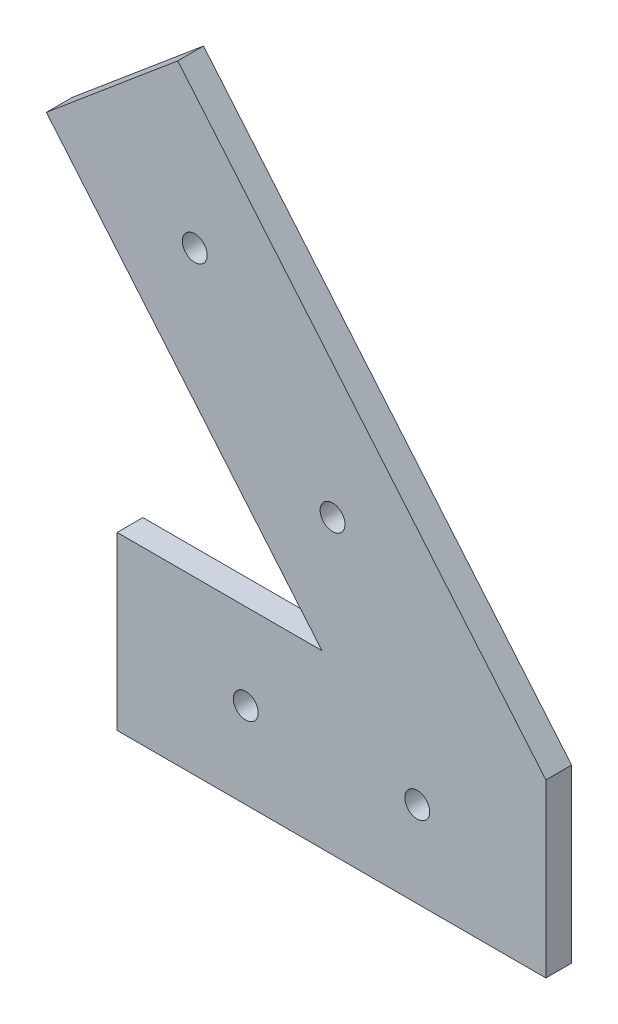
SolidWorks part; units mm, degrees
material "ABS"
ref_plane "Front Plane" through (0, 0, 0) normal (0, 0, 1) x (1, 0, 0)
ref_plane "Top Plane" through (0, 0, 0) normal (0, 1, 0) x (1, 0, 0)
ref_plane "Right Plane" through (0, 0, 0) normal (1, 0, 0) x (0, 0, -1)
sketch "Sketch1" plane through (0, 0, 0) normal (0, 0, 1) x (1, 0, 0)
  line L0 (0, 0) -> (32.1394, -38.3022)
  line L1 (32.1394, -38.3022) -> (8.2475, -38.3022)
  line L2 (8.2475, -38.3022) -> (8.2475, -58.3022)
  line L3 (8.2475, -58.3022) -> (58.2475, -58.3022)
  line L4 (58.2475, -58.3022) -> (58.2475, -38.3022)
  line L5 (58.2475, -38.3022) -> (15.3209, 12.8558)
  line L6 (0, 0) -> (15.3209, 12.8558)
  circle A0 centre (23.2475, -48.3022) radius 1.45
  circle A1 centre (43.2475, -48.3022) radius 1.45
  circle A2 centre (17.3023, -5.0628) radius 1.45
  circle A3 centre (33.3719, -24.2139) radius 1.45
  dimension "D6" = 2.9
  dimension "D1" = 20
  dimension "D2" = 20
  dimension "D3" = 50
  dimension "D4" = 50
  dimension "D5" = 50
  dimension "D7" = 15
  dimension "D8" = 25
  dimension "D9" = 15
  dimension "D10" = 15
extrude "Boss-Extrude1" add sketch "Sketch1" along normal blind 3
